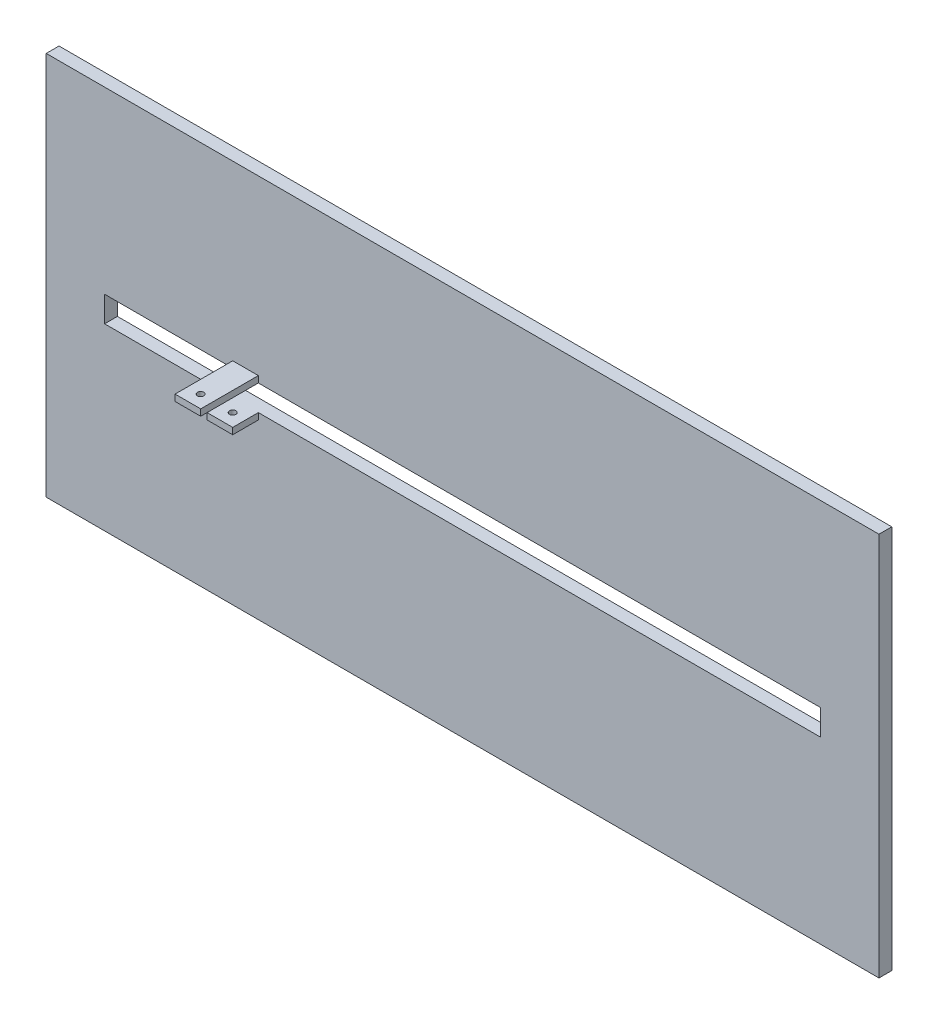
SolidWorks part; units mm, degrees
ref_plane "Front Plane" through (0, 0, 0) normal (0, 0, 1) x (1, 0, 0)
ref_plane "Top Plane" through (0, 0, 0) normal (0, 1, 0) x (1, 0, 0)
ref_plane "Right Plane" through (0, 0, 0) normal (1, 0, 0) x (0, 0, -1)
sketch "Sketch1" plane through (0, 0, 0) normal (0, 0, 1) x (1, 0, 0)
  line L1 (-650, 300) -> (650, 300)
  line L2 (-650, 300) -> (-650, -300)
  line L3 (-650, -300) -> (650, -300)
  line L4 (650, 300) -> (650, -300)
  line L5 (-650, 300) -> (650, -300) construction
  line L6 (-650, -300) -> (650, 300) construction
  line L7 (558.8382, 20) -> (-558.8382, 20)
  line L8 (558.8382, 20) -> (558.8382, -20)
  line L9 (-558.8382, 20) -> (-558.8382, -20)
  line L10 (-558.8382, -20) -> (558.8382, -20)
  point P0 (0, 0)
  point P10 (-547.2671, 20)
  point P12 (0, -20)
  dimension "D1" = 600
  dimension "D2" = 1300
extrude "Boss-Extrude1" add sketch "Sketch1" along normal blind 20
sketch "Sketch2" plane through (0, 0, 20) normal (0, 0, 1) x (1, 0, 0)
  line L1 (558.8382, 20) -> (-558.8382, 20) construction
  line L2 (-358.8382, 20) -> (-358.8382, 30)
  line L3 (-358.8382, 30) -> (-318.8382, 30)
  line L4 (-318.8382, 30) -> (-318.8382, 20)
  line L5 (-318.8382, 20) -> (-358.8382, 20)
  line L7 (-318.8382, -30) -> (-318.8382, -20)
  line L8 (-318.8382, -20) -> (-358.8382, -20)
  line L9 (-358.8382, -20) -> (-358.8382, -30)
  line L10 (-358.8382, -30) -> (-318.8382, -30)
  dimension "D1" = 10
  dimension "D2" = 40
extrude "Boss-Extrude2" add sketch "Sketch2" along normal blind 40
sketch "Sketch3" plane through (0, -30, 0) normal (0, -1, 0) x (1, 0, 0)
  circle A0 centre (-338.8382, 40) radius 5
  dimension "D1" = 10
extrude "Cut-Extrude1" cut sketch "Sketch3" against normal blind 10
sketch "Sketch4" plane through (0, 0, 60) normal (0, 0, 1) x (1, 0, 0)
  line L0 (-358.8382, 30) -> (-318.8382, 30)
  line L1 (-318.8382, 30) -> (-318.8382, 20)
  line L2 (-318.8382, 20) -> (-358.8382, 20)
  line L3 (-358.8382, 20) -> (-358.8382, 30)
extrude "Boss-Extrude3" add sketch "Sketch4" along normal blind 50
sketch "Sketch5" plane through (0, 20, 0) normal (0, -1, 0) x (1, 0, 0)
  circle A0 centre (-338.8382, 90) radius 5
  dimension "D2" = 10
extrude "Cut-Extrude2" cut sketch "Sketch5" against normal blind 10
